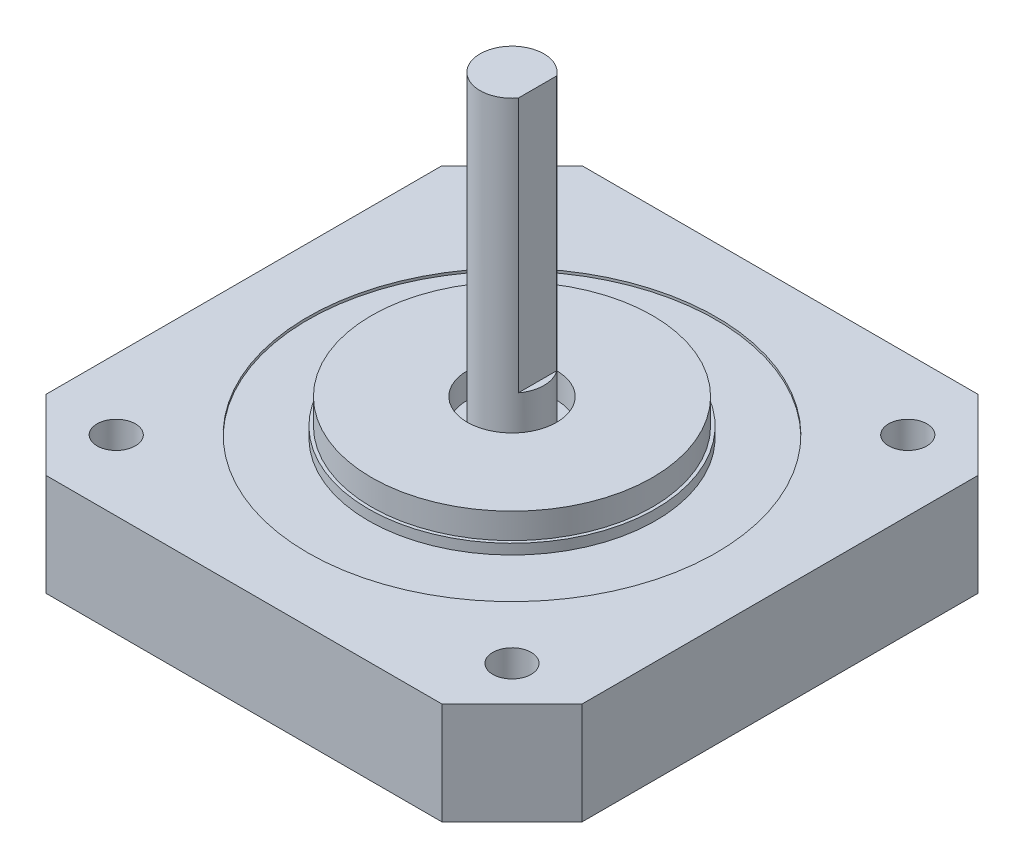
SolidWorks part; units mm, degrees
ref_plane "Front Plane" through (0, 0, 0) normal (0, 0, 1) x (1, 0, 0)
ref_plane "Top Plane" through (0, 0, 0) normal (0, 1, 0) x (1, 0, 0)
ref_plane "Right Plane" through (0, 0, 0) normal (1, 0, 0) x (0, 0, -1)
sketch "Sketch1" plane through (0, 0, 0) normal (0, 1, 0) x (1, 0, 0)
  line L1 (-21, 21) -> (21, 21)
  line L2 (-21, 21) -> (-21, -21)
  line L3 (-21, -21) -> (21, -21)
  line L4 (21, 21) -> (21, -21)
  line L5 (-21, 21) -> (21, -21) construction
  line L6 (-21, -21) -> (21, 21) construction
  point P0 (0, 0)
  dimension "D1" = 42
  dimension "D2" = 42
extrude "Nema 17" add sketch "Sketch1" along normal blind 8
chamfer "Chamfer1" distance 5.5 angle 45 4 edges at (-21, 4, -21) (21, 4, -21) (21, 4, 21) (-21, 4, 21)
sketch "Sketch2" plane through (0, 0, 0) normal (0, -1, 0) x (1, 0, 0)
  line L0 (-21, -15.5) -> (-21, 15.5) construction
  line L1 (15.5, -21) -> (-15.5, -21) construction
  line L2 (0, 0) -> (0, 21) construction
  line L4 (0, 0) -> (21, 0) construction
  circle A0 centre (-15.5, -15.5) radius 1.5
  circle A1 centre (15.5, -15.5) radius 1.5
  circle A2 centre (-15.5, 15.5) radius 1.5
  circle A3 centre (15.5, 15.5) radius 1.5
  dimension "D1" = 5.5
  dimension "D2" = 3
  dimension "D3" = 5.5
extrude "M3 Bolt Holes" cut sketch "Sketch2" against normal through all
sketch "Sketch3" plane through (0, 8, 0) normal (0, 1, 0) x (1, 0, 0)
  circle A0 centre (0, 0) radius 16
  dimension "D1" = 32
extrude "Cut-Extrude1" cut sketch "Sketch3" against normal blind 0.2
sketch "Sketch4" plane through (0, 7.8, 0) normal (0, 1, 0) x (1, 0, 0)
  circle A0 centre (0, 0) radius 11.25
  dimension "D1" = 22.5
extrude "Boss-Extrude1" add sketch "Sketch4" along normal blind 0.8
sketch "Sketch5" plane through (0, 8.6, 0) normal (0, 1, 0) x (1, 0, 0)
  circle A0 centre (0, 0) radius 11
  dimension "D1" = 22
extrude "Boss-Extrude2" add sketch "Sketch5" along normal blind 2
sketch "Sketch6" plane through (0, 8.6, 0) normal (0, 1, 0) x (1, 0, 0)
  circle A0 centre (0, 0) radius 3.5
  dimension "D1" = 7
extrude "Cut-Extrude2" cut sketch "Sketch6" along normal through all
sketch "Sketch7" plane through (0, 8.6, 0) normal (0, 1, 0) x (1, 0, 0)
  circle A0 centre (0, 0) radius 2.5
  dimension "D1" = 5
extrude "Boss-Extrude3" add sketch "Sketch7" along normal blind 24
sketch "Sketch9" plane through (0, 32.6, 0) normal (0, 1, 0) x (1, 0, 0)
  line L0 (2, 1.5) -> (2, -1.5)
  circle A0 centre (0, 0) radius 2.5 construction
  circle A1 centre (0, 0) radius 2.5 construction
  arc A2 (2, 1.5) -> (2, -1.5) centre (0, 0) cw
  dimension "D1" = 2
extrude "Cut-Extrude3" cut sketch "Sketch9" against normal blind 20
sketch "Sketch10" plane through (0, 0, 0) normal (0, -1, 0) x (1, 0, 0)
  circle A0 centre (15.5, 15.5) radius 1.5
  circle A1 centre (-15.5, -15.5) radius 1.5
  circle A2 centre (15.5, -15.5) radius 1.5
  circle A3 centre (-15.5, 15.5) radius 1.5
extrude "Boss-Extrude4" add sketch "Sketch10" against normal blind 1
